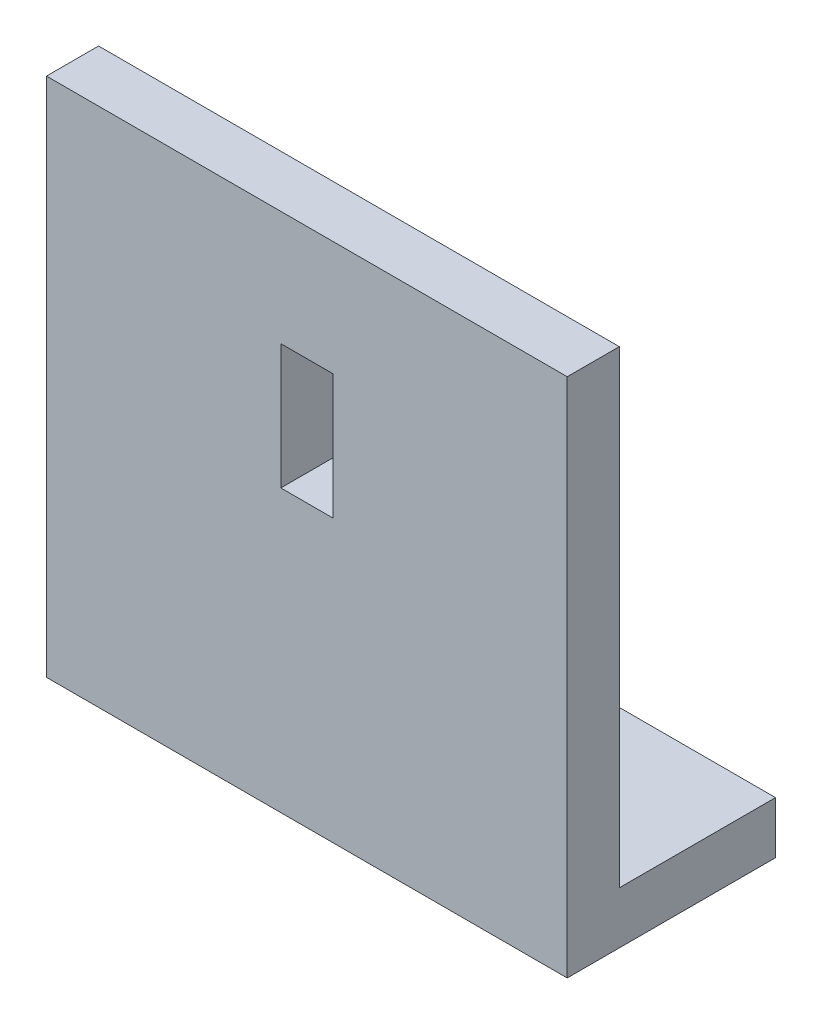
SolidWorks part; units mm, degrees
ref_plane "Front Plane" through (0, 0, 0) normal (0, 0, 1) x (1, 0, 0)
ref_plane "Top Plane" through (0, 0, 0) normal (0, 1, 0) x (1, 0, 0)
ref_plane "Right Plane" through (0, 0, 0) normal (1, 0, 0) x (0, 0, -1)
sketch "Sketch3" plane through (0, 0, 0) normal (0, 1, 0) x (1, 0, 0)
  line L1 (-50, 20) -> (50, 20)
  line L2 (-50, 20) -> (-50, -20)
  line L3 (-50, -20) -> (50, -20)
  line L4 (50, 20) -> (50, -20)
  line L5 (-50, 20) -> (50, -20) construction
  line L6 (-50, -20) -> (50, 20) construction
  point P0 (0, 0)
  dimension "D1" = 40
  dimension "D2" = 100
extrude "Boss-Extrude1" add sketch "Sketch3" along normal blind 10
sketch "Sketch4" plane through (0, 10, 0) normal (0, 1, 0) x (1, 0, 0)
  line L0 (50, -20) -> (50, 20) construction
  line L1 (-50, -20) -> (50, -20)
  line L2 (-50, -20) -> (-50, -10)
  line L3 (-50, -10) -> (50, -10)
  line L4 (50, -20) -> (50, -10)
  dimension "D1" = 10
extrude "Boss-Extrude2" add sketch "Sketch4" along normal blind 90
sketch "Sketch5" plane through (0, 10, 0) normal (0, 1, 0) x (1, 0, 0)
  line L0 (-50, 20) -> (-50, 5) construction
  line L1 (-50, 20) -> (-50, -10) construction
  line L2 (-50, 5) -> (0, 5) construction
  line L3 (0, 5) -> (0, 11.7831) construction
  circle A0 centre (-25, 5) radius 2
  circle A1 centre (25, 5) radius 2
  dimension "D1" = 4
extrude "Cut-Extrude1" cut sketch "Sketch5" against normal blind 90
sketch "Sketch7" plane through (0, 0, 10) normal (0, 0, -1) x (-1, 0, 0)
  line L0 (-50, 100) -> (0, 100) construction
  line L1 (-50, 100) -> (50, 100) construction
  line L2 (0, 100) -> (0, 60) construction
  line L3 (-1.1659, 59.0562) -> (1.1659, 59.0562) construction
  line L5 (-5, 66) -> (5, 66)
  line L6 (-5, 66) -> (-5, 54)
  line L7 (-5, 54) -> (5, 54)
  line L8 (5, 66) -> (5, 54)
  line L9 (-5, 66) -> (5, 54) construction
  line L10 (-5, 54) -> (5, 66) construction
  arc A0 (1.1659, 59.0562) -> (-1.1659, 59.0562) centre (0, 60) ccw construction
  dimension "D1" = 3
  dimension "D2" = 10
  dimension "D3" = 12
extrude "Cut-Extrude3" cut sketch "Sketch7" against normal blind 10
sketch "Sketch8" plane through (0, 0, 10) normal (0, 0, -1) x (-1, 0, 0)
  line L0 (-5, 54) -> (-5, 66)
  line L1 (-5, 66) -> (-7, 66)
  line L2 (-7, 66) -> (-7, 52)
  line L3 (-7, 52) -> (7, 52)
  line L4 (7, 52) -> (7, 66)
  line L5 (7, 66) -> (5, 66)
  line L6 (5, 66) -> (5, 54)
  line L7 (5, 54) -> (-5, 54)
  dimension "D1" = 2
  dimension "D2" = 2
  dimension "D3" = 2
extrude "Boss-Extrude3" add sketch "Sketch8" along normal blind 23
sketch "Sketch9" plane through (0, 54, 0) normal (0, 1, 0) x (1, 0, 0)
  line L0 (-5, 13) -> (-5, -10) construction
  line L1 (5, 13) -> (-5, 13)
  line L2 (5, 13) -> (5, 11)
  line L3 (5, 11) -> (-5, 11)
  line L4 (-5, 13) -> (-5, 11)
  dimension "D1" = 2
extrude "Boss-Extrude5" add sketch "Sketch9" along normal blind 12
sketch "Sketch12" plane through (0, 66, 0) normal (0, 1, 0) x (1, 0, 0)
  line L0 (-7, 13) -> (-7, -10) construction
  line L1 (-5, 11) -> (-7, 11)
  line L2 (-5, 11) -> (-5, 4)
  line L3 (-5, 4) -> (-7, 4)
  line L4 (-7, 11) -> (-7, 4)
  dimension "D1" = 7
extrude "Cut-Extrude6" cut sketch "Sketch12" against normal blind 12
sketch "Sketch13" plane through (0, 0, 10) normal (0, 0, -1) x (-1, 0, 0)
  line L1 (-5, 66) -> (5, 66)
  line L2 (-5, 66) -> (-5, 78)
  line L3 (-5, 78) -> (5, 78)
  line L4 (5, 66) -> (5, 78)
  dimension "D1" = 12
extrude "Cut-Extrude7" cut sketch "Sketch13" against normal blind 10
